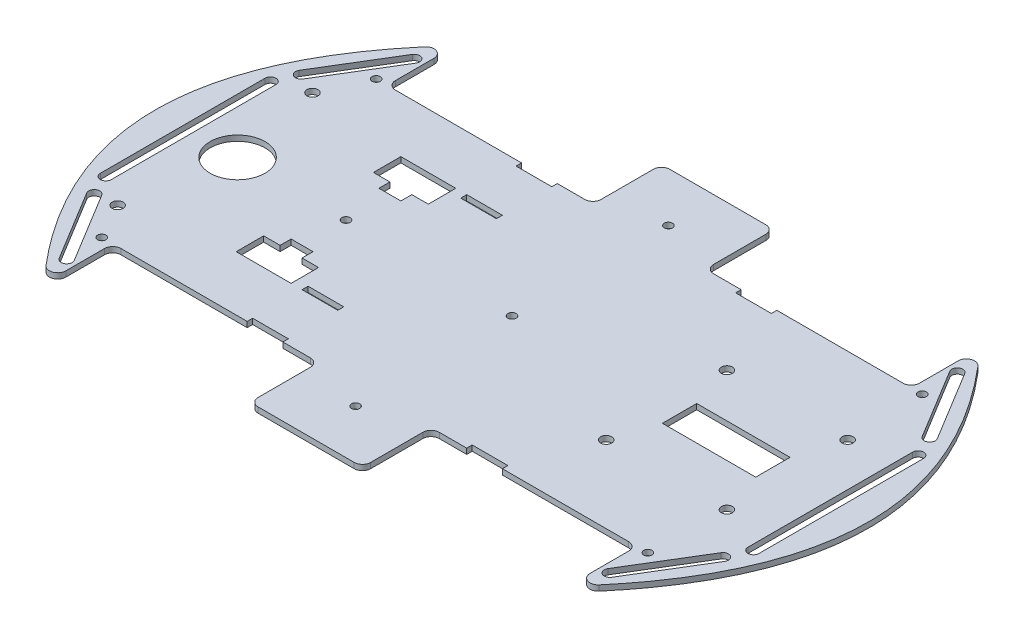
SolidWorks part; units mm, degrees
ref_plane "Front Plane" through (0, 0, 0) normal (0, 0, 1) x (1, 0, 0)
ref_plane "Top Plane" through (0, 0, 0) normal (0, 1, 0) x (1, 0, 0)
ref_plane "Right Plane" through (0, 0, 0) normal (1, 0, 0) x (0, 0, -1)
sketch "Sketch1" plane through (0, 0, 0) normal (0, 1, 0) x (1, 0, 0)
  line L0 (-95.5, 75) -> (-95.5, -75) construction
  line L1 (-130, 75) -> (130, 75)
  line L2 (-130, 75) -> (-130, -75)
  line L3 (-130, -75) -> (130, -75)
  line L4 (130, 75) -> (130, -75)
  line L5 (-130, 75) -> (130, -75) construction
  line L6 (-130, -75) -> (130, 75) construction
  line L7 (0, 83.5132) -> (0, -90.0376) construction
  line L8 (-95.5, 75) -> (-95.5, 50)
  line L9 (-95.5, 50) -> (-20.5, 50)
  line L10 (-20.5, 50) -> (-20.5, 75)
  line L11 (-20.5, 75) -> (0, 75)
  line L12 (20.5, 50) -> (20.5, 75)
  line L13 (95.5, 75) -> (95.5, 50)
  line L14 (95.5, 50) -> (20.5, 50)
  line L16 (95.5, -75) -> (95.5, -50)
  line L17 (95.5, -50) -> (20.5, -50)
  line L18 (20.5, -50) -> (20.5, -75)
  line L19 (-20.5, -50) -> (-20.5, -75)
  line L20 (-95.5, -50) -> (-20.5, -50)
  line L21 (-95.5, -75) -> (-95.5, -50)
  line L22 (-46.5, 50) -> (-46.5, 48)
  line L23 (-46.5, 48) -> (-33.5, 48)
  line L24 (-33.5, 48) -> (-33.5, 50)
  line L26 (-46.5, 30) -> (-33.5, 30)
  line L29 (-46.5, 30) -> (-46.5, 27.8038)
  line L30 (-46.5, 27.8038) -> (-33.5, 27.8038)
  line L31 (-33.5, 27.8038) -> (-33.5, 30)
  line L32 (-33.5, -27.8038) -> (-33.5, -30)
  line L33 (-46.5, -30) -> (-46.5, -27.8038)
  line L34 (-46.5, -30) -> (-33.5, -30)
  line L35 (-46.5, -27.8038) -> (-33.5, -27.8038)
  line L44 (-50.5, 30) -> (-70.5, 30)
  line L45 (-70.5, 30) -> (-70.5, 20)
  line L46 (-70.5, 20) -> (-64.5, 20)
  line L47 (-50.5, 30) -> (-50.5, 20)
  line L48 (-50.5, 20) -> (-56.5, 20)
  line L49 (-64.5, 20) -> (-64.5, 16)
  line L50 (-56.5, 20) -> (-56.5, 16)
  line L51 (-56.5, 16) -> (-64.5, 16)
  line L52 (-56.5, -20) -> (-56.5, -16)
  line L53 (-50.5, -20) -> (-56.5, -20)
  line L54 (-50.5, -30) -> (-50.5, -20)
  line L55 (-50.5, -30) -> (-70.5, -30)
  line L56 (-70.5, -30) -> (-70.5, -20)
  line L57 (-70.5, -20) -> (-64.5, -20)
  line L58 (-64.5, -20) -> (-64.5, -16)
  line L59 (-56.5, -16) -> (-64.5, -16)
  line L76 (-70.5, 25) -> (-169.0961, 25) construction
  line L77 (-120, 85.6828) -> (-120, -92.3992) construction
  line L78 (-118, 92.3992) -> (-118, -92.3992) construction
  line L79 (-118, 30) -> (-118, -30) construction
  line L80 (-116, 30) -> (-116, -30)
  line L81 (-120, 30) -> (-120, -30)
  line L82 (-118, 32) -> (-95.5, 69)
  line L83 (-114.5437, 37.6837) -> (-98.9563, 63.3163) construction
  line L86 (0, 75) -> (0, 57)
  line L87 (-116.2526, 38.7228) -> (-100.6651, 64.3555)
  line L88 (-112.8349, 36.6445) -> (-97.2474, 62.2772)
  line L89 (-114.5437, -37.6837) -> (-98.9563, -63.3163) construction
  line L90 (-116.2526, -38.7228) -> (-100.6651, -64.3555)
  line L91 (-112.8349, -36.6445) -> (-97.2474, -62.2772)
  line L92 (114.5437, -37.6837) -> (98.9563, -63.3163) construction
  line L93 (116.2526, -38.7228) -> (100.6651, -64.3555)
  line L94 (112.8349, -36.6445) -> (97.2474, -62.2772)
  line L95 (118, 30) -> (118, -30) construction
  line L96 (116, 30) -> (116, -30)
  line L97 (120, 30) -> (120, -30)
  line L98 (114.5437, 37.6837) -> (98.9563, 63.3163) construction
  line L99 (116.2526, 38.7228) -> (100.6651, 64.3555)
  line L100 (112.8349, 36.6445) -> (97.2474, 62.2772)
  line L101 (-100, 0) -> (-100, 80.5994) construction
  line L102 (-33.5, -48) -> (-33.5, -50)
  line L107 (-46.5, -48) -> (-33.5, -48)
  line L108 (-46.5, -50) -> (-46.5, -48)
  line L109 (46.5, -50) -> (46.5, -48)
  line L110 (46.5, -48) -> (33.5, -48)
  line L111 (33.5, -48) -> (33.5, -50)
  line L112 (33.5, 48) -> (33.5, 50)
  line L113 (46.5, 48) -> (33.5, 48)
  line L114 (46.5, 50) -> (46.5, 48)
  line L115 (61.3108, 6) -> (95.3108, 6)
  line L116 (61.3108, 6) -> (61.3108, -6.5)
  line L117 (61.3108, -6.5) -> (95.3108, -6.5)
  line L118 (95.3108, 6) -> (95.3108, -6.5)
  circle A0 centre (-100, 0) radius 10
  circle A2 centre (-99.5, 50) radius 1.5
  circle A3 centre (-99.5, -50) radius 1.5
  circle A4 centre (99.5, -50) radius 1.5
  circle A5 centre (99.5, 50) radius 1.5
  arc A6 (-116, 30) -> (-120, 30) centre (-118, 30) ccw
  arc A7 (-120, -30) -> (-116, -30) centre (-118, -30) ccw
  circle A10 centre (0, 57) radius 1.5
  circle A11 centre (0, -57) radius 1.5
  arc A12 (-116.2526, 38.7228) -> (-112.8349, 36.6445) centre (-114.5437, 37.6837) ccw
  arc A13 (-97.2474, 62.2772) -> (-100.6651, 64.3555) centre (-98.9563, 63.3163) ccw
  arc A14 (-116.2526, -38.7228) -> (-112.8349, -36.6445) centre (-114.5437, -37.6837) cw
  arc A15 (-97.2474, -62.2772) -> (-100.6651, -64.3555) centre (-98.9563, -63.3163) cw
  arc A16 (116.2526, -38.7228) -> (112.8349, -36.6445) centre (114.5437, -37.6837) ccw
  arc A17 (97.2474, -62.2772) -> (100.6651, -64.3555) centre (98.9563, -63.3163) ccw
  arc A18 (116, 30) -> (120, 30) centre (118, 30) cw
  arc A19 (120, -30) -> (116, -30) centre (118, -30) cw
  arc A20 (116.2526, 38.7228) -> (112.8349, 36.6445) centre (114.5437, 37.6837) cw
  arc A21 (97.2474, 62.2772) -> (100.6651, 64.3555) centre (98.9563, 63.3163) cw
  circle A22 centre (0, 0) radius 1.5
  circle A24 centre (-60.5, 0) radius 1.5
  circle A25 centre (56.3108, 22) radius 2
  circle A27 centre (56.3108, -22) radius 2
  circle A28 centre (100.3108, 22) radius 2
  circle A29 centre (100.3108, -22) radius 2
  circle A30 centre (-106.75, 34.0364) radius 2
  circle A31 centre (-106.75, -36.9636) radius 2
  spline S0 degree 2 poles (-95.5, 75) (-164.5, 0) (-95.5, -75) knots 0 0 0 1 1 1
  spline S1 degree 2 poles (95.5, 75) (164.5, 0) (95.5, -75) knots 0 0 0 1 1 1
  point P0 (0, 0)
  point P73 (0, 0)
  point P74 (0, 0)
  point P75 (-106.75, 32.9443)
  point P76 (0, 0)
  point P77 (0, 0)
  point P78 (0, 0)
  point P79 (0, 0)
  point P80 (0, 0)
  point P99 (-118, 0)
  point P102 (-118, 0)
  point P111 (-106.75, 50.5)
  point P122 (-106.75, -50.5)
  point P129 (106.75, -50.5)
  point P136 (118, 0)
  point P143 (106.75, 50.5)
  dimension "D11" = 20
  dimension "D20" = 3
  dimension "D30" = 3
  dimension "D31" = 3
  dimension "D32" = 100
  dimension "D33" = 28
  dimension "D42" = 4
  dimension "D43" = 4
  dimension "D1" = 260
  dimension "D2" = 150
  dimension "D3" = 34.5
  dimension "D4" = 25
  dimension "D5" = 75
  dimension "D6" = 2
  dimension "D7" = 13
  dimension "D8" = 13
  dimension "D9" = 20
  dimension "D10" = 20.1962
  dimension "D12" = 30
  dimension "D13" = 4
  dimension "D14" = 20
  dimension "D15" = 10
  dimension "D16" = 6
  dimension "D17" = 6
  dimension "D18" = 10
  dimension "D19" = 4
  dimension "D21" = 4
  dimension "D22" = 10
  dimension "D23" = 12
  dimension "D24" = 4
  dimension "D25" = 60
  dimension "D26" = 6
  dimension "D27" = 4
  dimension "D28" = 30
  dimension "D29" = 18
  dimension "D34" = 44
  dimension "D35" = 28
  dimension "D36" = 44
  dimension "44" = 44
  dimension "D37" = 44
  dimension "D38" = 12.5
  dimension "D39" = 5
  dimension "24" = 34
  dimension "D40" = 44
  dimension "D41" = 71
extrude "Boss-Extrude1" add sketch "Sketch1" along normal blind 2
fillet "Fillet1" radius 3 16 edges at (-20.5, 1, -50) (-20.5, 1, -75) (95.5, 1, -75) (20.5, 1, -75) (20.5, 1, -50) (95.5, 1, -50) (95.5, 1, 75) (95.5, 1, 50) (20.5, 1, 50) (20.5, 1, 75) (-20.5, 1, 75) (-20.5, 1, 50) (-95.5, 1, 50) (-95.5, 1, -50) (-95.5, 1, -75) (-95.5, 1, 75)
